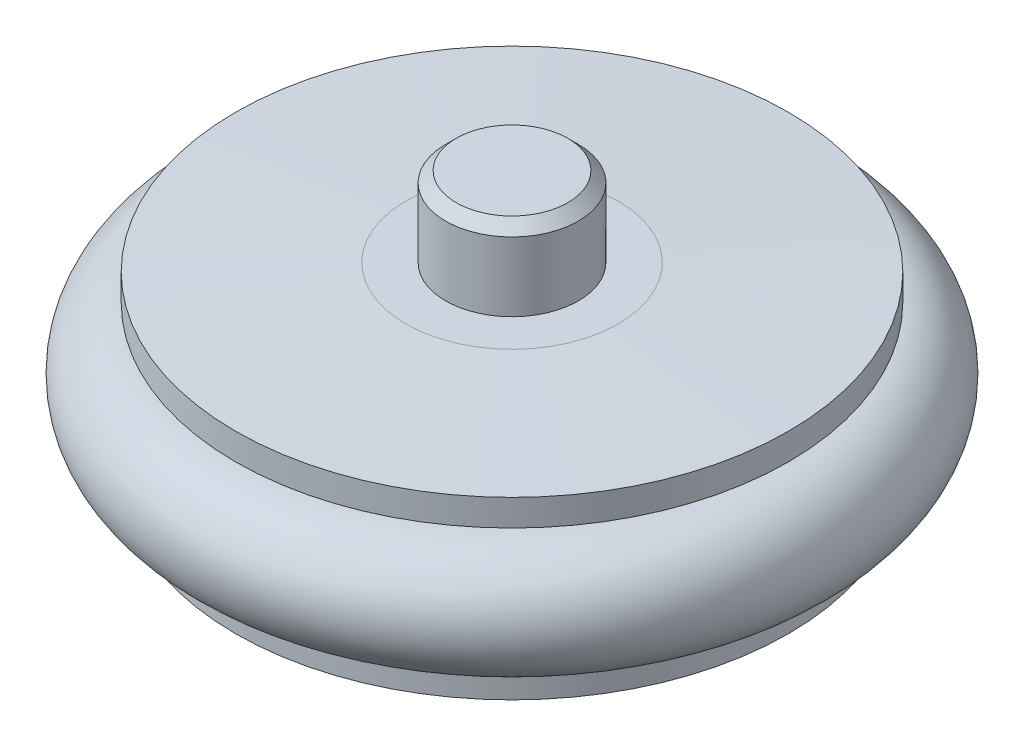
SolidWorks part; units mm, degrees
material "6061 Alloy"
ref_plane "Front Plane" through (0, 0, 0) normal (0, 0, 1) x (1, 0, 0)
ref_plane "Top Plane" through (0, 0, 0) normal (0, 1, 0) x (1, 0, 0)
ref_plane "Right Plane" through (0, 0, 0) normal (1, 0, 0) x (0, 0, -1)
sketch "Sketch1" plane through (0, 0, 0) normal (0, 0, 1) x (1, 0, 0)
  line L0 (1.05, 3.3) -> (0, 3.3)
  line L1 (0, 3.3) -> (0, -3.3)
  line L2 (0, -3.3) -> (1.05, -3.3)
  line L3 (1.05, -3.3) -> (1.25, -3.1)
  line L4 (1.25, -3.1) -> (1.25, -1.8)
  line L5 (1.25, -1.8) -> (2, -1.8)
  line L6 (2, -1.8) -> (5.2, -1.65)
  line L7 (5.2, -1.65) -> (5.2, -1.15)
  line L8 (5.2, -1.15) -> (3.9, -1.15)
  line L9 (3.9, -1.15) -> (3.9, 1.15)
  line L10 (3.9, 1.15) -> (5.2, 1.15)
  line L11 (5.2, 1.15) -> (5.2, 1.65)
  line L12 (5.2, 1.65) -> (2, 1.8)
  line L13 (2, 1.8) -> (1.25, 1.8)
  line L14 (1.25, 1.8) -> (1.25, 3.1)
  line L15 (1.25, 3.1) -> (1.05, 3.3)
  line L16 (0, 3.3) -> (0, -3.3) construction
  point P16 (0, 0)
  point P17 (3.9, 0)
  dimension "D1" = 6.6
  dimension "D2" = 1.05
  dimension "D3" = 1.25
  dimension "D4" = 2.3
  dimension "D5" = 0.5
  dimension "D6" = 0.5
  dimension "D8" = 1.05
  dimension "D9" = 0.75
  dimension "D10" = 3.9
  dimension "D11" = 5.2
  dimension "D13" = 1.3
  dimension "D14" = 1.3
revolve "Revolve1" add sketch "Sketch1" angle 360 about L16
sketch "Sketch2" plane through (0, 0, 0) normal (0, 0, 1) x (1, 0, 0)
  line L0 (0, 5.5201) -> (0, -5.808) construction
  circle A0 centre (5.1, 0) radius 1.1
  dimension "D1" = 5.1
revolve "Revolve2" add sketch "Sketch2" angle 360 about L0
